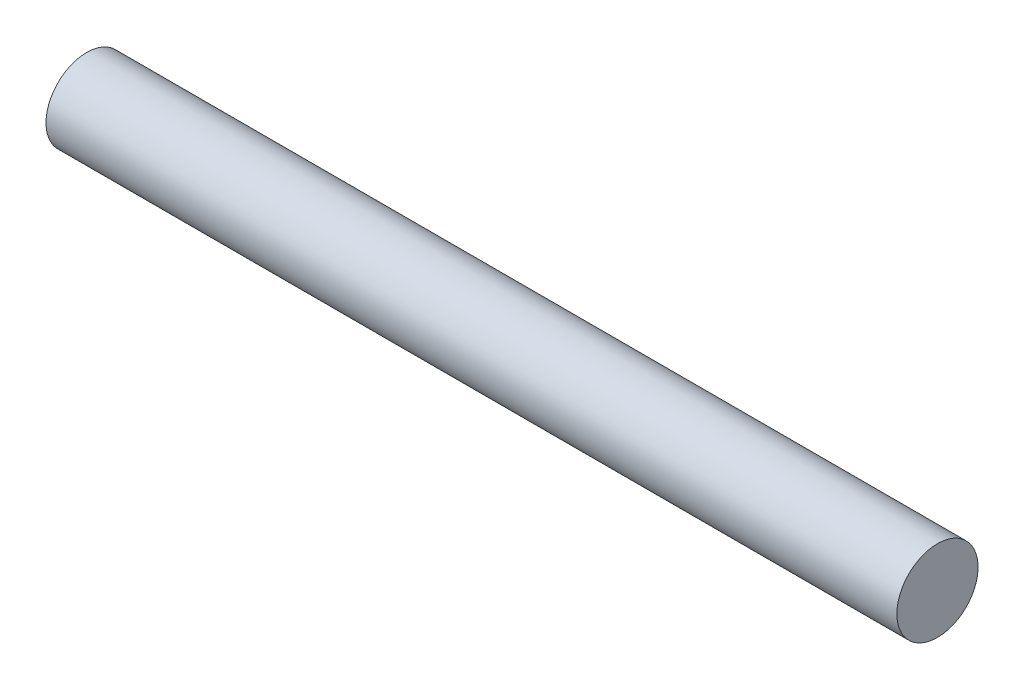
SolidWorks part; units mm, degrees
ref_plane "Front Plane" through (0, 0, 0) normal (0, 0, 1) x (1, 0, 0)
ref_plane "Top Plane" through (0, 0, 0) normal (0, 1, 0) x (1, 0, 0)
ref_plane "Right Plane" through (0, 0, 0) normal (1, 0, 0) x (0, 0, -1)
sketch "Sketch1" plane through (0, 0, 0) normal (0, 0, 1) x (1, 0, 0)
  line L0 (0, 0) -> (52.36, 0) construction
  line L1 (52.36, 0) -> (52.36, 2.5)
  line L2 (52.36, 2.5) -> (0, 2.5)
  line L3 (0, 2.5) -> (0, 0)
  line L4 (0, 0) -> (52.36, 0)
  dimension "D1" = 5
  dimension "D2" = 52.36
revolve "Revolve1" add sketch "Sketch1" angle 360 about L0
